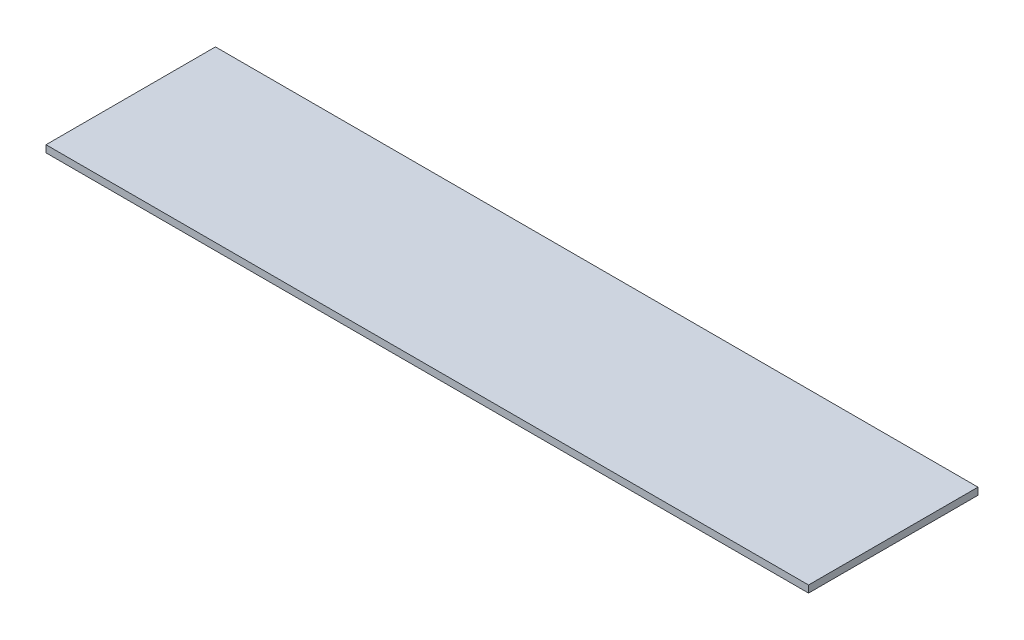
SolidWorks part; units mm, degrees
ref_plane "Front Plane" through (0, 0, 0) normal (0, 0, 1) x (1, 0, 0)
ref_plane "Top Plane" through (0, 0, 0) normal (0, 1, 0) x (1, 0, 0)
ref_plane "Right Plane" through (0, 0, 0) normal (1, 0, 0) x (0, 0, -1)
other "Configuration Table"
sketch "Sketch1" plane through (0, 0, 0) normal (0, 1, 0) x (1, 0, 0)
  line L0 (-685.8, -152.4) -> (685.8, 152.4) construction
  line L1 (-685.8, 152.4) -> (685.8, 152.4)
  line L2 (-685.8, 152.4) -> (-685.8, -152.4)
  line L3 (-685.8, -152.4) -> (685.8, -152.4)
  line L4 (685.8, 152.4) -> (685.8, -152.4)
  dimension "D1" = 1371.6
  dimension "D2" = 304.8
extrude "Extrude1" add sketch "Sketch1" against normal blind 12.7
